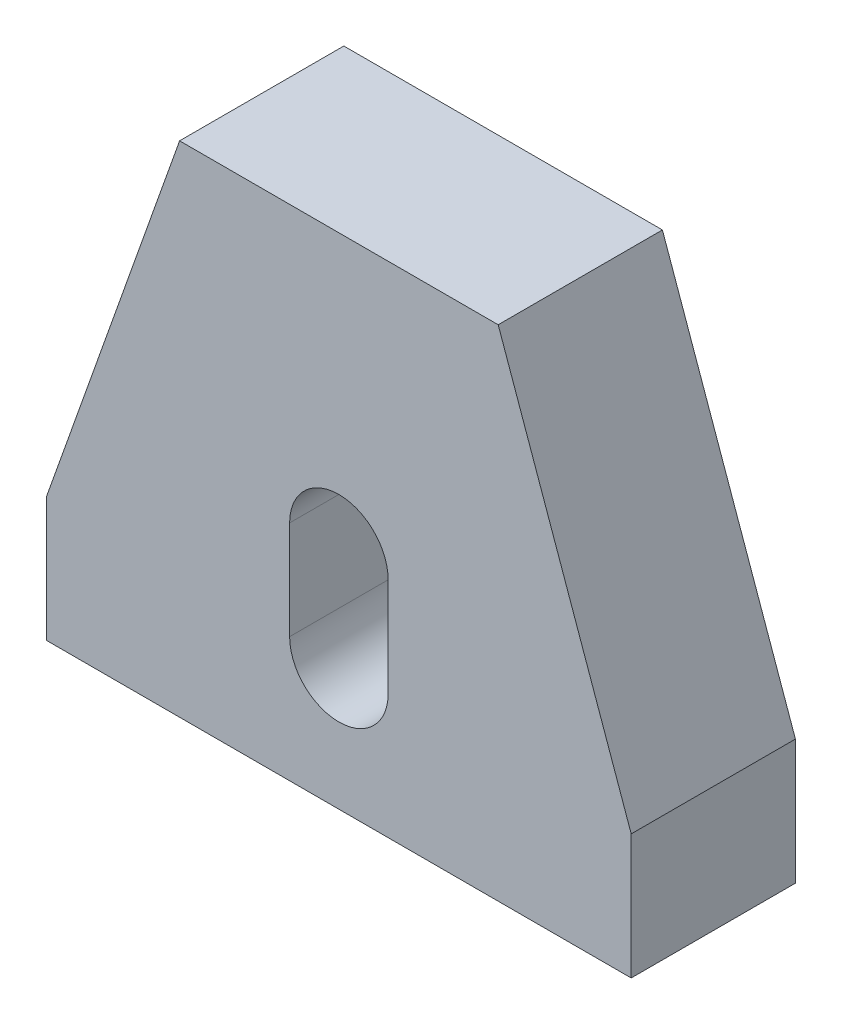
SolidWorks part; units mm, degrees
ref_plane "Front Plane" through (0, 0, 0) normal (0, 0, 1) x (1, 0, 0)
ref_plane "Top Plane" through (0, 0, 0) normal (0, 1, 0) x (1, 0, 0)
ref_plane "Right Plane" through (0, 0, 0) normal (1, 0, 0) x (0, 0, -1)
sketch "Sketch1" plane through (0, 0, 0) normal (0, 0, 1) x (1, 0, 0)
  line L0 (-4.85, 8.4) -> (4.85, 8.4)
  line L1 (4.85, 8.4) -> (8.9, -3)
  line L2 (8.9, -3) -> (8.9, -6.8)
  line L3 (8.9, -6.8) -> (-8.9, -6.8)
  line L4 (-8.9, -6.8) -> (-8.9, -3)
  line L5 (-8.9, -3) -> (-4.85, 8.4)
  line L6 (-8.9, -3) -> (8.9, -3) construction
  line L7 (0, 0) -> (0, -3) construction
  line L8 (1.5, 0) -> (1.5, -3)
  line L9 (-1.5, 0) -> (-1.5, -3)
  arc A0 (1.5, 0) -> (-1.5, 0) centre (0, 0) ccw
  arc A1 (-1.5, -3) -> (1.5, -3) centre (0, -3) ccw
  point P9 (0, -1.5)
  dimension "D1" = 9.7
  dimension "D2" = 4.85
  dimension "D3" = 17.8
  dimension "D4" = 8.9
  dimension "D5" = 3.8
  dimension "D6" = 15.2
  dimension "D7" = 3
  dimension "D8" = 3
  dimension "D9" = 3.8
extrude "Boss-Extrude1" add sketch "Sketch1" along normal mid plane 5
equation "\"D2@Sketch1\"=\"D1@Sketch1\"/2"
equation "\"D4@Sketch1\"=\"D3@Sketch1\"/2"
